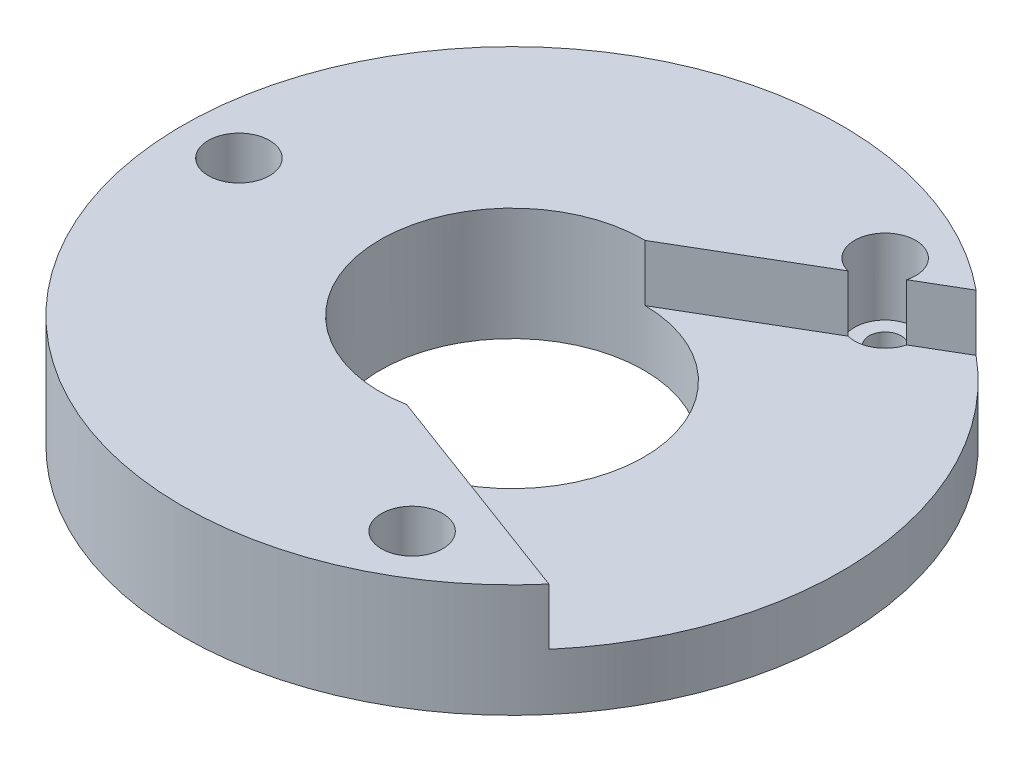
SolidWorks part; units mm, degrees
material "ABS"
ref_plane "前视基准面" through (0, 0, 0) normal (0, 0, 1) x (1, 0, 0)
ref_plane "上视基准面" through (0, 0, 0) normal (0, 1, 0) x (1, 0, 0)
ref_plane "右视基准面" through (0, 0, 0) normal (1, 0, 0) x (0, 0, -1)
sketch "草图1" plane through (0, 0, 0) normal (0, 1, 0) x (1, 0, 0)
  line L0 (0, 0) -> (14.5, 25.1147) construction
  line L1 (0, 0) -> (0, 35) construction
  circle A0 centre (0, 0) radius 35
  circle A1 centre (14.5, 25.1147) radius 1.7
  circle A2 centre (14.5, -25.1147) radius 1.7
  circle A3 centre (-29, 0) radius 1.7
  dimension "D1" = 70
  dimension "D5" = 3.4
  dimension "D2" = 29
  dimension "D3" = 30
  dimension "D4" = 3
extrude "凸台-拉伸1" add sketch "草图1" along normal blind 12
sketch "草图2" plane through (0, 12, 0) normal (0, 1, 0) x (1, 0, 0)
  line L6 (-4.1851, -11.2465) -> (41.3059, -28.1748)
  line L7 (0, 0) -> (50, 0) construction
  line L8 (0, 0) -> (40.9576, 28.6788) construction
  line L9 (-6.0745, 10.349) -> (35.7859, 34.9195)
  line L10 (0, 0) -> (45.3154, -21.1309) construction
  circle A0 centre (45.3154, -21.1309) radius 8 construction
  circle A5 centre (0, 0) radius 12
  circle A6 centre (0, 0) radius 50
  circle A7 centre (40.9576, 28.6788) radius 8 construction
  dimension "D1" = 35
  dimension "D2" = 25
  dimension "D4" = 24
  dimension "D6" = 16
  dimension "D5" = 50
extrude "切除-拉伸1" cut sketch "草图2" against normal blind 6
sketch "草图4" plane through (0, 0, 0) normal (0, -1, 0) x (1, 0, 0)
  circle A0 centre (0, 0) radius 14
  dimension "D1" = 28
extrude "切除-拉伸3" cut sketch "草图4" against normal through all
sketch "草图5" plane through (0, 12, 0) normal (0, 1, 0) x (1, 0, 0)
  circle A0 centre (14.5, 25.1147) radius 3.25
  circle A1 centre (14.5, -25.1147) radius 3.25
  circle A2 centre (-29, 0) radius 3.25
  dimension "D1" = 6.5
extrude "切除-拉伸4" cut sketch "草图5" against normal blind 8
